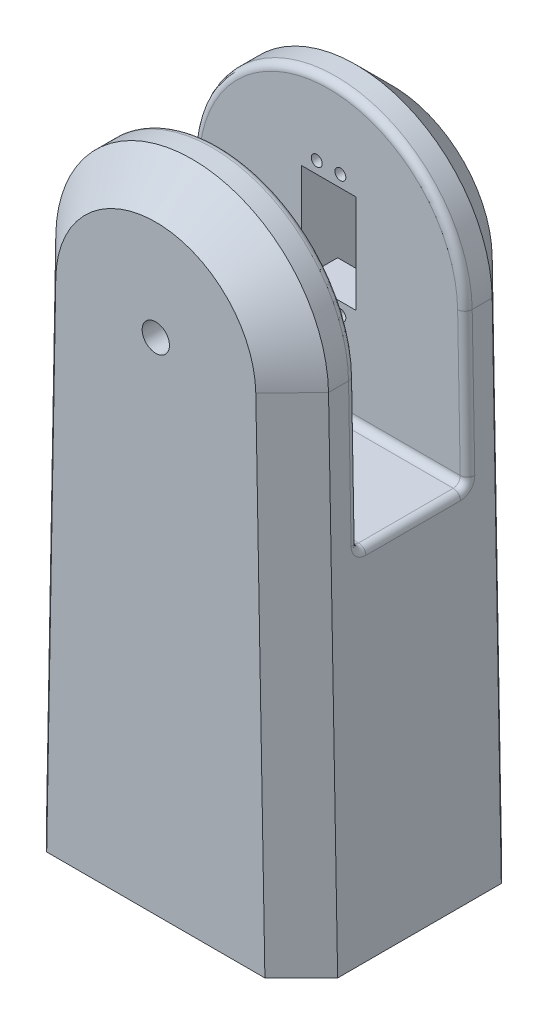
SolidWorks part; units mm, degrees
ref_plane "Front Plane" through (0, 0, 0) normal (0, 0, 1) x (1, 0, 0)
ref_plane "Top Plane" through (0, 0, 0) normal (0, 1, 0) x (1, 0, 0)
ref_plane "Right Plane" through (0, 0, 0) normal (1, 0, 0) x (0, 0, -1)
sketch "Sketch1" plane through (0, 0, 0) normal (0, 0, 1) x (1, 0, 0)
  line L0 (-40, 0) -> (40, 0)
  line L1 (0, -1000) -> (0, 49000) construction
  line L2 (40, 0) -> (37.4938, 138.18)
  line L3 (-40, 0) -> (-37.4938, 138.18)
  arc A0 (37.4938, 138.18) -> (-37.4938, 138.18) centre (0, 137.5) ccw
  point P4 (0, 0)
  dimension "D2" = 75
  dimension "D1" = 80
  dimension "D3" = 137.5
extrude "Boss-Extrude1" add sketch "Sketch1" along normal blind 65
chamfer "Chamfer1" distance 10 6 edges at (-38.7469, 69.09, 0) (38.7469, 69.09, 0) (0, 175, 0) (-38.7469, 69.09, 65) (0, 175, 65) (38.7469, 69.09, 65)
sketch "Sketch2" plane through (0, 0, 0) normal (0, -1, 0) x (-1, 0, 0)
  line L0 (40, -32.5) -> (-40, -32.5) construction
  line L1 (40, -55) -> (40, -10) construction
  line L2 (-40, -55) -> (-40, -10) construction
  circle A0 centre (0, -32.5) radius 15
  dimension "D1" = 30
extrude "Cut-Extrude1" cut sketch "Sketch2" against normal blind 5
sketch "Sketch4" plane through (0, 5, 0) normal (0, -1, 0) x (1, 0, 0)
  line L0 (-15, 32.5) -> (15, 32.5) construction
  line L1 (0, 47.5) -> (0, 17.5) construction
  circle A0 centre (0, 32.5) radius 15 construction
  circle A1 centre (0, 32.5) radius 15 construction
  circle A2 centre (0, 40) radius 1.5
  circle A3 centre (7.5, 32.5) radius 1.5
  circle A4 centre (0, 25) radius 1.5
  circle A5 centre (-7.5, 32.5) radius 1.5
  point P11 (0, 32.5)
  point P12 (0, 0)
  point P13 (0, 0)
  point P21 (0, 32.5)
  dimension "D1" = 3
  dimension "D2" = 7.5
  dimension "D3" = 4
extrude "Cut-Extrude2" cut sketch "Sketch4" against normal blind 7.5
fillet "Fillet1" radius 1 2 edges at (0, 5, 17.5) (0, 0, 17.5)
sketch "Sketch5" plane through (0, 0, 0) normal (1, 0, 0) x (0, 0, -1)
  line L0 (-32.5, -1000) -> (-32.5, 49000) construction
  line L1 (-55, 0) -> (-10, 0) construction
  line L3 (-47.5, 175) -> (-17.5, 175)
  line L4 (-47.5, 175) -> (-47.5, 97)
  line L5 (-47.5, 97) -> (-17.5, 97)
  line L6 (-17.5, 175) -> (-17.5, 97)
  line L7 (-47.5, 175) -> (-17.5, 97) construction
  line L8 (-47.5, 97) -> (-17.5, 175) construction
  line L9 (-10, 175) -> (-55, 175) construction
  point P1 (-32.5, 136)
  point P5 (-32.5, 0)
  dimension "D1" = 78
  dimension "D2" = 30
extrude "Cut-Extrude3" cut sketch "Sketch5" along normal mid plane 89.5
fillet "Fillet2" radius 2 10 edges at (37.8673, 117.59, 17.5) (-37.8673, 117.59, 17.5) (-37.8673, 117.59, 47.5) (37.8673, 117.59, 47.5) (0, 175, 17.5) (0, 175, 47.5) (-38.2407, 97, 32.5) (38.2407, 97, 32.5) (0, 97, 17.5) (0, 97, 47.5)
sketch "Sketch6" plane through (0, 0, 0) normal (0, 0, -1) x (-1, 0, 0)
  line L1 (-7.5, 157.5) -> (7.5, 157.5)
  line L2 (-7.5, 157.5) -> (-7.5, 117.5)
  line L3 (-7.5, 117.5) -> (7.5, 117.5)
  line L4 (7.5, 157.5) -> (7.5, 117.5)
  line L5 (-7.5, 157.5) -> (7.5, 117.5) construction
  line L6 (-7.5, 117.5) -> (7.5, 157.5) construction
  point P0 (0, 137.5)
  dimension "D1" = 40
  dimension "D2" = 15
extrude "Cut-Extrude4" cut sketch "Sketch6" against normal offset from surface (7.5 mm away) 10 up to face at (0, 127.2859, 17.5)
sketch "Sketch7" plane through (0, 0, 7.5) normal (0, 0, -1) x (-1, 0, 0)
  line L0 (7.5, 117.5) -> (7.5, 157.5) construction
  line L1 (-7.5, 157.5) -> (7.5, 157.5)
  line L2 (-7.5, 157.5) -> (-7.5, 151)
  line L3 (-7.5, 151) -> (7.5, 151)
  line L4 (7.5, 157.5) -> (7.5, 151)
  line L5 (-7.5, 157.5) -> (-7.5, 117.5) construction
  line L6 (7.5, 117.5) -> (-7.5, 117.5)
  line L7 (7.5, 117.5) -> (7.5, 124)
  line L8 (7.5, 124) -> (-7.5, 124)
  line L9 (-7.5, 117.5) -> (-7.5, 124)
  line L10 (-7.5, 151) -> (-7.5, 124)
  line L11 (7.5, 124) -> (7.5, 151)
  line L12 (0, 157.5) -> (0, 117.5) construction
  line L13 (-7.5, 137.5) -> (7.5, 137.5) construction
  circle A0 centre (-3.25, 154.25) radius 1.5
  circle A1 centre (3.25, 154.25) radius 1.5
  circle A2 centre (3.25, 120.75) radius 1.5
  circle A3 centre (-3.25, 120.75) radius 1.5
  line M10 (7.5, 117.5) -> (7.5, 157.5)
  line M12 (-7.5, 157.5) -> (-7.5, 117.5)
  dimension "D3" = 3
  dimension "D1" = 6.5
  dimension "D2" = 6.5
  dimension "D4" = 3.25
  dimension "D5" = 3.25
extrude "Cut-Extrude5" cut sketch "Sketch7" against normal up to surface (10 mm away) contours L8 L3 M10 M12 | A0 | A1 | A3 | A2 up to face at (0, 127.2859, 17.5)
sketch "Sketch8" plane through (0, 0, 0) normal (0, 0, -1) x (-1, 0, 0)
  line L0 (0, 157.5) -> (0, 117.5) construction
  line L1 (7.5, 157.5) -> (-7.5, 157.5) construction
  line L2 (-7.5, 117.5) -> (7.5, 117.5) construction
  circle A0 centre (0, 137.5) radius 3.75
  dimension "D1" = 7.5
extrude "Cut-Extrude6" cut sketch "Sketch8" against normal through all
